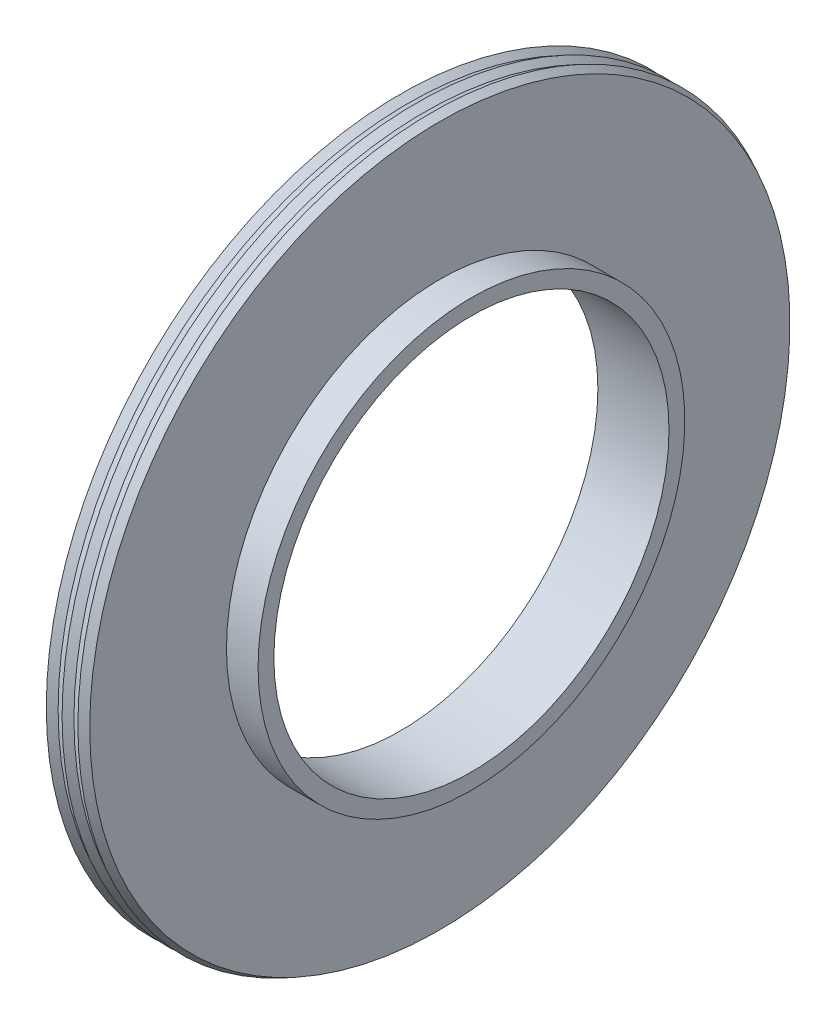
SolidWorks part; units mm, degrees
ref_plane "前视基准面" through (0, 0, 0) normal (0, 0, 1) x (1, 0, 0)
ref_plane "上视基准面" through (0, 0, 0) normal (0, 1, 0) x (1, 0, 0)
ref_plane "右视基准面" through (0, 0, 0) normal (1, 0, 0) x (0, 0, -1)
other "Configuration Table"
sketch "草图1" plane through (0, 0, 0) normal (0, 0, 1) x (1, 0, 0)
  line L0 (-26.2689, 0) -> (123.1353, 0) construction
  line L1 (0, 0) -> (0, 25)
  line L2 (0, 25) -> (9, 25)
  line L3 (9, 25) -> (9, 27)
  line L4 (9, 27) -> (0, 27)
  line L5 (0, 27) -> (0, 25)
  line L6 (0, 0) -> (0, 44.8)
  line L7 (0, 44.8) -> (5, 44.8)
  line L8 (5, 44.8) -> (5, 27)
  line L10 (0, 44.8) -> (1, 44.3)
  line L11 (1, 44.3) -> (2, 44.8)
  line L12 (2, 44.8) -> (3, 44.3)
  line L13 (3, 44.3) -> (4, 44.8)
  line L14 (4, 44.8) -> (5, 44.3)
  dimension "D1" = 25
  dimension "D2" = 9
  dimension "D3" = 2
  dimension "D4" = 5
  dimension "D5" = 44.8
  dimension "D6" = 17.8
  dimension "D8" = 1
  dimension "D9" = 1
  dimension "D10" = 1
  dimension "D11" = 1
revolve "旋转1" add sketch "草图1" angle 360 about L0
